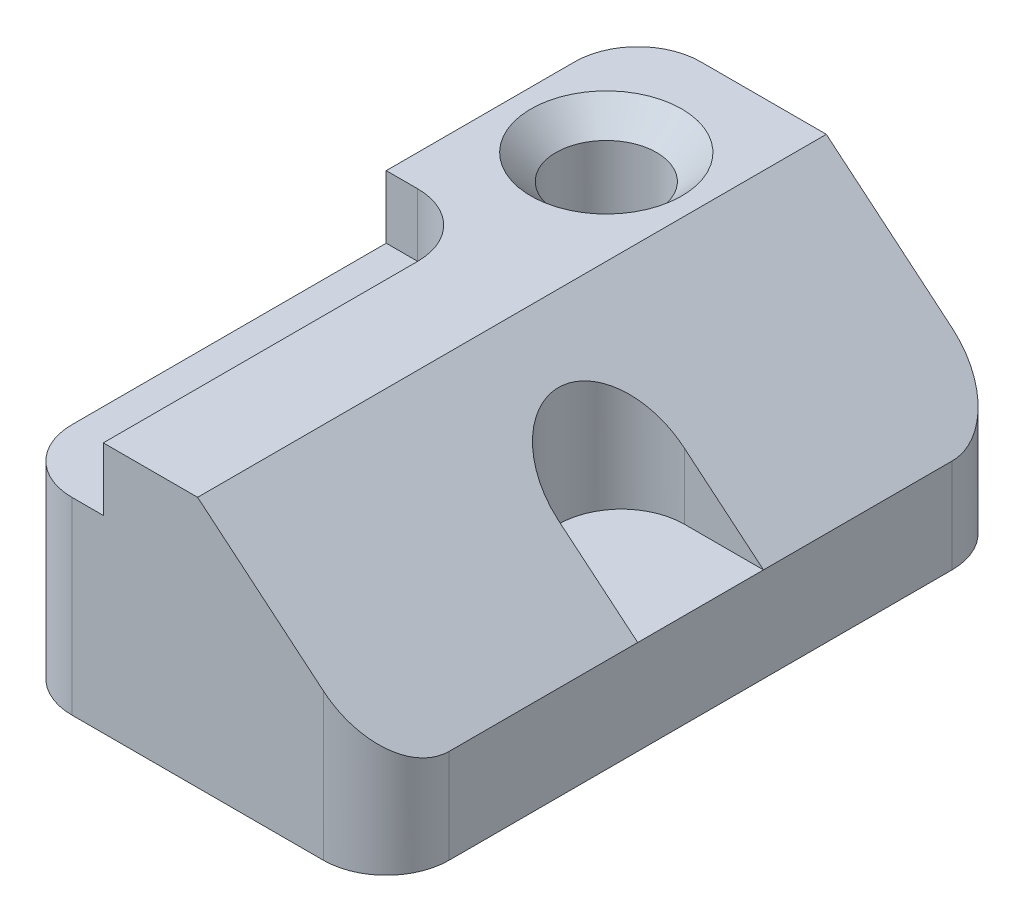
SolidWorks part; units mm, degrees
material "Plain Carbon Steel"
ref_plane "Front Plane" through (0, 0, 0) normal (0, 0, 1) x (1, 0, 0)
ref_plane "Top Plane" through (0, 0, 0) normal (0, 1, 0) x (1, 0, 0)
ref_plane "Right Plane" through (0, 0, 0) normal (1, 0, 0) x (0, 0, -1)
sketch "Sketch1" plane through (0, 0, 0) normal (0, 0, 1) x (1, 0, 0)
  line L0 (0, 0) -> (0, 50.8)
  line L1 (0, 50.8) -> (38.1, 50.8)
  line L2 (38.1, 50.8) -> (76.2, 19.05)
  line L3 (76.2, 19.05) -> (76.2, 0)
  line L4 (76.2, 0) -> (0, 0)
  dimension "D1" = 38.1
  dimension "D2" = 50.8
  dimension "D3" = 19.05
  dimension "D4" = 76.2
extrude "Boss-Extrude1" add sketch "Sketch1" along normal blind 127
sketch "Sketch2" plane through (0, 50.8, 0) normal (0, 1, 0) x (1, 0, 0)
  line L0 (38.1, 0) -> (0, 0) construction
  line L1 (0, -127) -> (0, 0) construction
  circle A0 centre (19.05, -25.4) radius 10.16
  dimension "D3" = 20.32
  dimension "D1" = 25.4
  dimension "D2" = 19.05
extrude "Cut-Extrude1" cut sketch "Sketch2" against normal through all contours A0
chamfer "Chamfer1" distance 5.08 angle 45 1 edges at (19.05, 50.8, 35.56)
sketch "Sketch3" plane through (0, 50.8, 0) normal (0, 1, 0) x (1, 0, 0)
  line L0 (0, -127) -> (0, 0) construction
  line L1 (0, -50.8) -> (19.05, -50.8)
  line L2 (0, -50.8) -> (0, -127)
  line L3 (0, -127) -> (19.05, -127)
  line L4 (19.05, -50.8) -> (19.05, -127)
  line L5 (38.1, -127) -> (0, -127) construction
  dimension "D1" = 19.05
  dimension "D2" = 76.2
extrude "Cut-Extrude2" cut sketch "Sketch3" against normal blind 12.7
fillet "Fillet1" radius 12.7 1 edges at (19.05, 44.45, 50.8)
sketch "Sketch4" plane through (0, 50.8, 0) normal (0, 1, 0) x (1, 0, 0)
  line L0 (76.2, -50.8) -> (60.198, -50.8)
  line L1 (76.2, -127) -> (76.2, 0) construction
  line L2 (60.198, -76.2) -> (76.2, -76.2)
  line L4 (76.2, -63.5) -> (0, -63.5) construction
  line L5 (0, -50.8) -> (0, -127) construction
  line L6 (76.2, -50.8) -> (76.2, -76.2)
  arc A0 (60.198, -50.8) -> (60.198, -76.2) centre (60.198, -63.5) ccw
  dimension "D1" = 12.7
  dimension "D2" = 16.002
extrude "Cut-Extrude4" cut sketch "Sketch4" against normal up to vertex (31.75 mm away) contours L2 L6 L0 A0
fillet "Fillet2" radius 12.7 4 edges at (0, 25.4, 0) (76.2, 9.525, 0) (0, 19.05, 127) (76.2, 9.525, 127)
